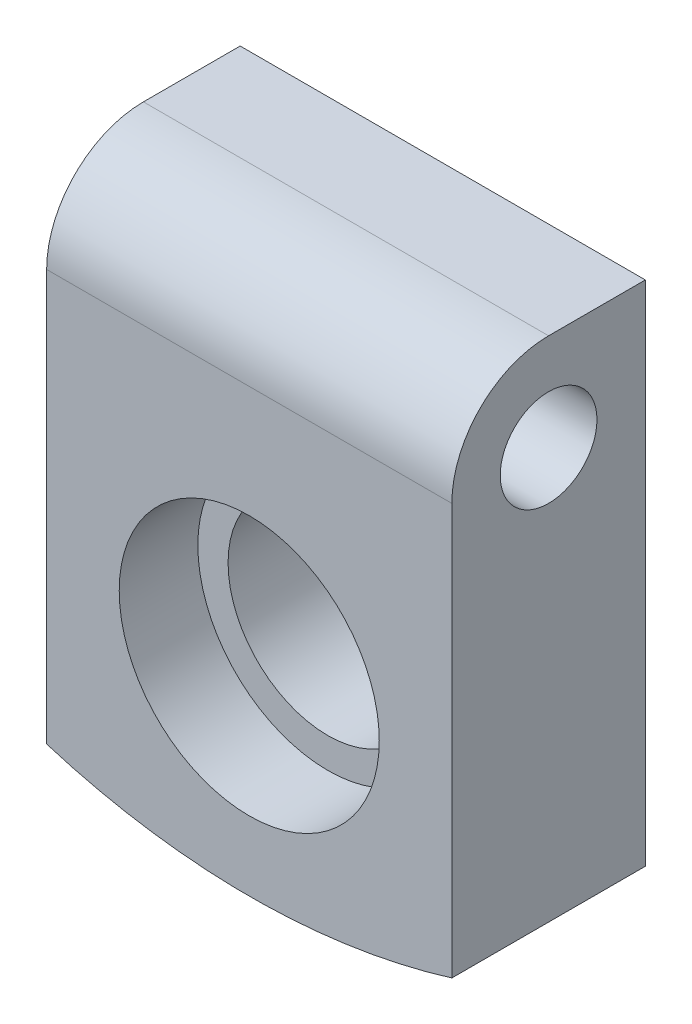
SolidWorks part; units mm, degrees
ref_plane "Ön Düzlem" through (0, 0, 0) normal (0, 0, 1) x (1, 0, 0)
ref_plane "Üst Düzlem" through (0, 0, 0) normal (0, 1, 0) x (1, 0, 0)
ref_plane "Sağ Düzlem" through (0, 0, 0) normal (1, 0, 0) x (0, 0, -1)
sketch "Çizim1" plane through (0, 0, 0) normal (0, 0, 1) x (1, 0, 0)
  line L0 (0, 0) -> (0, -89) construction
  line L1 (-33.5, 0) -> (33.5, 0)
  line L2 (33.5, 0) -> (33.5, -83.9667)
  line L3 (-33.5, 0) -> (-33.5, -83.9667)
  arc A1 (-33.5, -83.9667) -> (33.5, -83.9667) centre (0, 25) ccw
  dimension "D1" = 67
extrude "Yükseklik-Ekstrüzyon1" add sketch "Çizim1" along normal mid plane 32
sketch "Çizim2" plane through (0, 0, 0) normal (1, 0, 0) x (0, 0, -1)
  line L3 (-16, -83.9667) -> (-16, 0) construction
  line L4 (-16, 0) -> (16, 0) construction
  line L5 (-16, -16) -> (-16, 0)
  line L6 (-16, 0) -> (0, 0)
  arc A1 (-16, -16) -> (0, 0) centre (0, -16) cw
  dimension "D2" = 16
extrude "Kes-Ekstrüzyon1" cut sketch "Çizim2" against normal through all both and the other way through all
sketch "Çizim3" plane through (0, 0, 0) normal (1, 0, 0) x (0, 0, -1)
  circle A0 centre (0, -16) radius 8
extrude "Kes-Ekstrüzyon2" cut sketch "Çizim3" against normal through all both and the other way through all
sketch "Çizim4" plane through (0, 0, 0) normal (1, 0, 0) x (0, 0, -1)
  line L0 (-16, -56) -> (16, -56) construction
  line L1 (-16, -83.9667) -> (-16, -16) construction
  line L2 (16, -83.9667) -> (16, 0) construction
  line L3 (-16, -89) -> (16, -89) construction
  line L4 (-16, -34.5) -> (-3, -34.5)
  line L5 (-3, -34.5) -> (-3, -39.5)
  line L6 (-3, -39.5) -> (16, -39.5)
  line L7 (16, -56) -> (16, -39.5)
  line L8 (-16, -34.5) -> (-16, -56)
  line L9 (-16, -56) -> (16, -56)
  dimension "D1" = 33
  dimension "D2" = 21.5
  dimension "D3" = 16.5
  dimension "D4" = 13
revolve "Kes-Döndür1" cut sketch "Çizim4" angle 360 about L0
